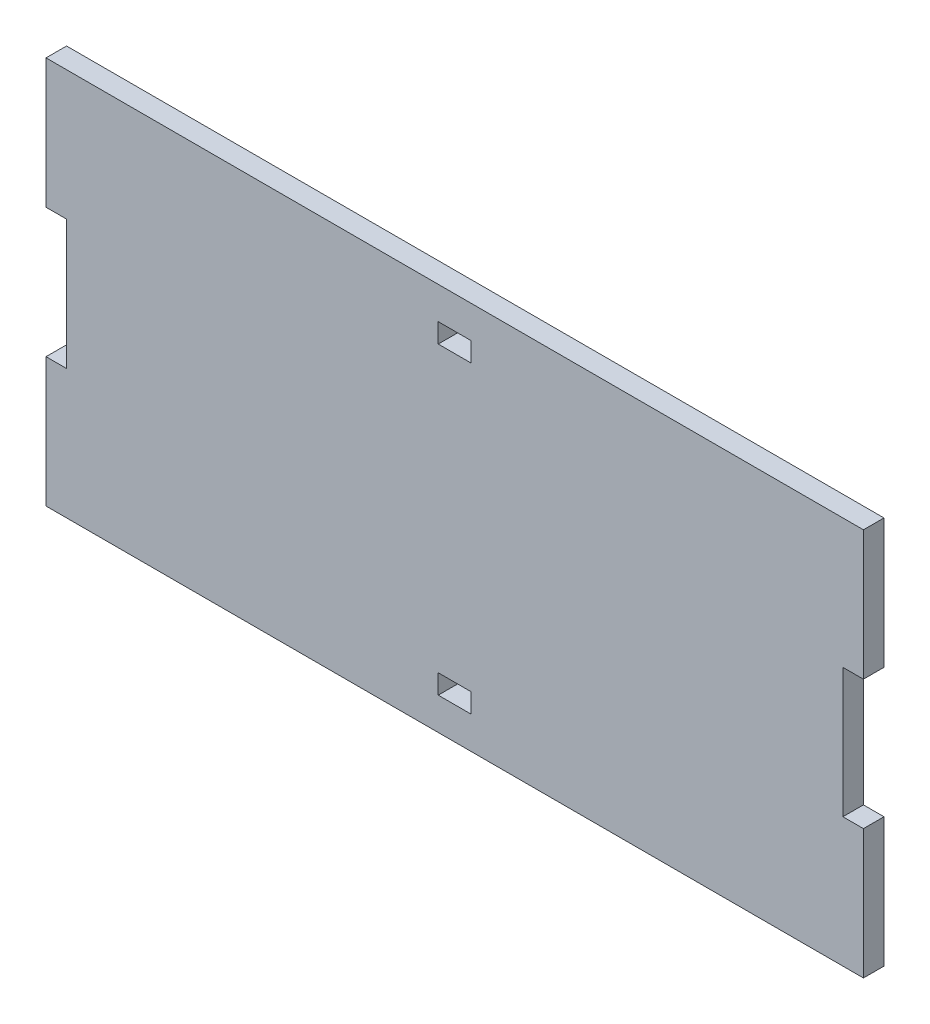
SolidWorks part; units mm, degrees
ref_plane "Front Plane" through (0, 0, 0) normal (0, 0, 1) x (1, 0, 0)
ref_plane "Top Plane" through (0, 0, 0) normal (0, 1, 0) x (1, 0, 0)
ref_plane "Right Plane" through (0, 0, 0) normal (1, 0, 0) x (0, 0, -1)
sketch "Sketch1" plane through (0, 0, 0) normal (0, 0, 1) x (1, 0, 0)
  line L0 (0, 40) -> (3.175, 40)
  line L1 (0, 0) -> (126.35, 0)
  line L2 (0, 0) -> (0, 20)
  line L3 (0, 60) -> (126.35, 60)
  line L4 (126.35, 0) -> (126.35, 20)
  line L5 (3.175, 40) -> (3.175, 20)
  line L6 (3.175, 20) -> (0, 20)
  line L7 (0, 40) -> (0, 60)
  line L8 (126.35, 40) -> (123.175, 40)
  line L9 (123.175, 40) -> (123.175, 20)
  line L10 (123.175, 20) -> (126.35, 20)
  line L11 (126.35, 40) -> (126.35, 60)
  line L12 (63.175, 0) -> (63.175, 5) construction
  line L13 (63.175, 60) -> (63.175, 55) construction
  line L15 (65.725, 8) -> (60.625, 8)
  line L16 (65.725, 8) -> (65.725, 5)
  line L17 (65.725, 5) -> (60.625, 5)
  line L18 (60.625, 8) -> (60.625, 5)
  line L19 (65.725, 52) -> (60.625, 52)
  line L20 (65.725, 52) -> (65.725, 55)
  line L21 (65.725, 55) -> (60.625, 55)
  line L22 (60.625, 52) -> (60.625, 55)
  point P26 (63.175, 55)
  point P28 (0, 0)
  dimension "D1" = 60
  dimension "D2" = 126.35
  dimension "D3" = 3.175
  dimension "D4" = 3.175
  dimension "D5" = 5.1
  dimension "D6" = 3
  dimension "D7" = 3
  dimension "D8" = 5.1
  dimension "D9" = 5
  dimension "D10" = 5
extrude "Boss-Extrude1" add sketch "Sketch1" along normal blind 3.175
